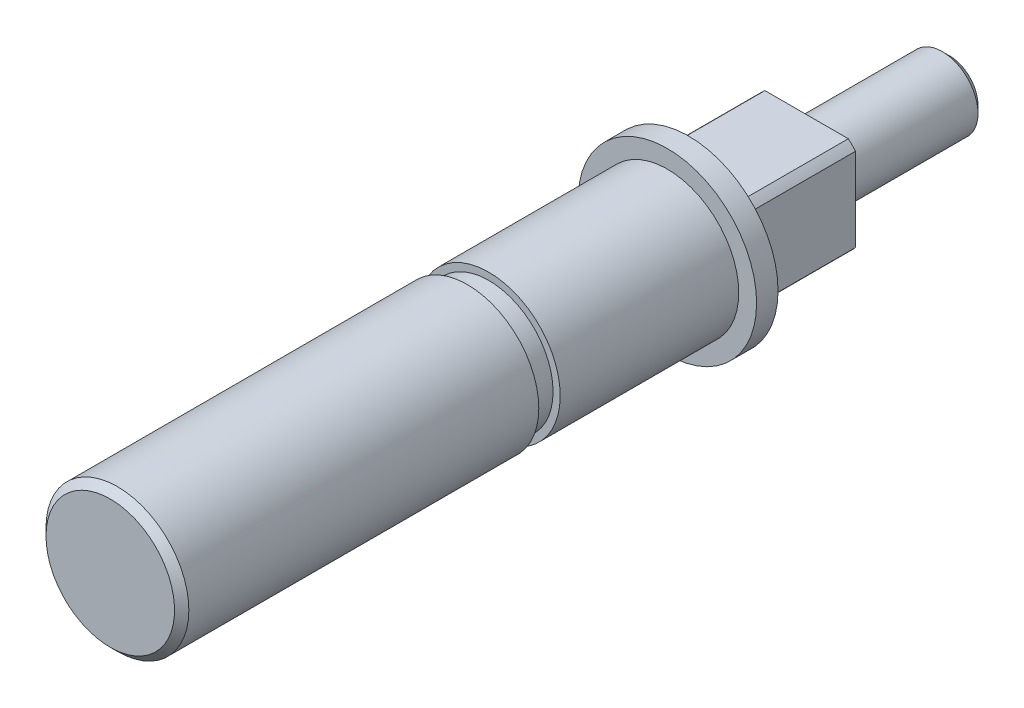
SolidWorks part; units mm, degrees
ref_plane "前视基准面" through (0, 0, 0) normal (0, 0, 1) x (1, 0, 0)
ref_plane "上视基准面" through (0, 0, 0) normal (0, 1, 0) x (1, 0, 0)
ref_plane "右视基准面" through (0, 0, 0) normal (1, 0, 0) x (0, 0, -1)
sketch "草图1" plane through (0, 0, 0) normal (1, 0, 0) x (0, 0, -1)
  line L0 (-117.5, 0) -> (0, 0)
  line L1 (0, 0) -> (0, 5)
  line L2 (0, 5) -> (-20, 5)
  line L3 (-20, 5) -> (-20, 9)
  line L4 (-20, 9) -> (-36.5, 9)
  line L5 (-36.5, 9) -> (-36.5, 12.5)
  line L6 (-36.5, 12.5) -> (-39.5, 12.5)
  line L7 (-39.5, 12.5) -> (-39.5, 10)
  line L8 (-39.5, 10) -> (-64.5, 10)
  line L9 (-64.5, 9) -> (-67.5, 9)
  line L10 (-67.5, 9) -> (-67.5, 10)
  line L11 (-67.5, 10) -> (-117.5, 10)
  line L12 (-64.5, 10) -> (-64.5, 9)
  line L13 (-117.5, 10) -> (-117.5, 0)
  dimension "D1" = 5
  dimension "D2" = 20
  dimension "D3" = 9
  dimension "D4" = 16.5
  dimension "D5" = 3
  dimension "D6" = 12.5
  dimension "D7" = 10
  dimension "D8" = 25
  dimension "D9" = 9
  dimension "D10" = 3
  dimension "D11" = 10
  dimension "D12" = 117.5
revolve "旋转1" add sketch "草图1" angle 360 about L0
cosmetic thread "装饰螺纹线1" parameters "D2"=18
cosmetic thread "装饰螺纹线2" parameters "D2"=8
sketch "草图2" plane through (0, 0, 20) normal (0, 0, -1) x (-1, 0, 0)
  line L0 (0, 0) -> (0, 7.5064) construction
  line L1 (-6.85, 6.85) -> (6.85, 6.85)
  line L2 (-6.85, 6.85) -> (-6.85, -6.85)
  line L3 (-6.85, -6.85) -> (6.85, -6.85)
  line L4 (6.85, 6.85) -> (6.85, -6.85)
  line L5 (0, 0) -> (17.1917, 0) construction
  dimension "D1" = 13.7
extrude "切除-拉伸1" cut sketch "草图2" against normal up to surface (16.5 mm away) flip side to cut up to face at (12.5, 0, 36.5)
chamfer "倒角1" distance 1 angle 45 2 edges at (5, 0, 0) (10, 0, 117.5)
